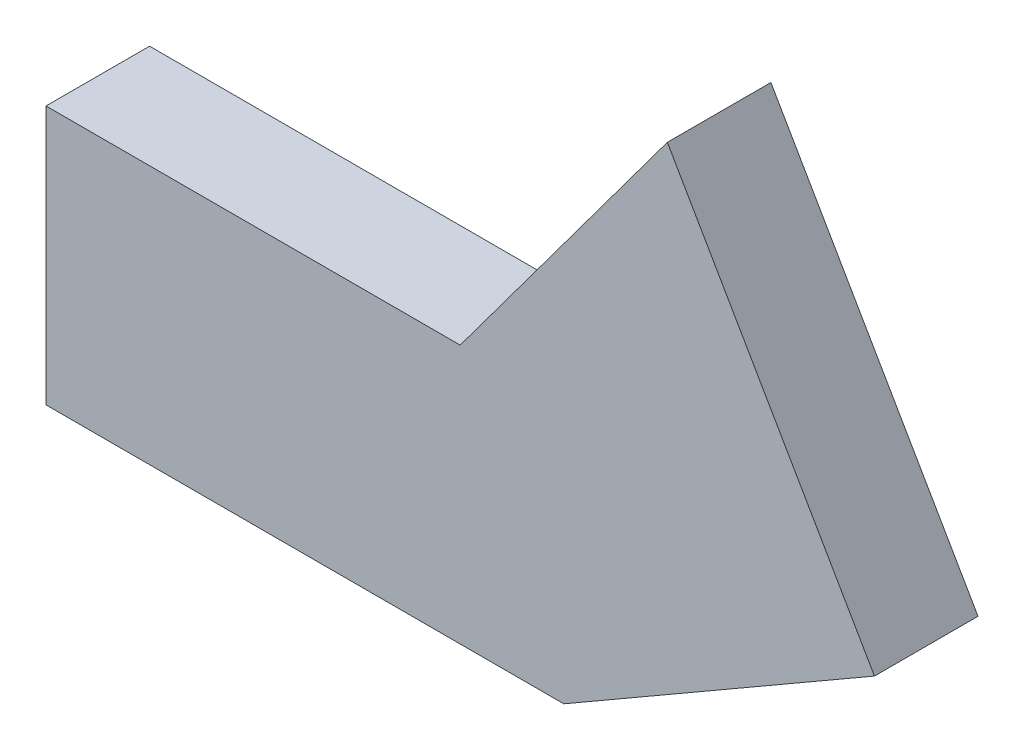
SolidWorks part; units mm, degrees
ref_plane "Front Plane" through (0, 0, 0) normal (0, 0, 1) x (1, 0, 0)
ref_plane "Top Plane" through (0, 0, 0) normal (0, 1, 0) x (1, 0, 0)
ref_plane "Right Plane" through (0, 0, 0) normal (1, 0, 0) x (0, 0, -1)
sketch "Sketch1" plane through (0, 0, 0) normal (0, 0, 1) x (1, 0, 0)
  line L7 (0, 0) -> (100, 0)
  line L8 (100, 0) -> (160, 34.641)
  line L9 (0, 0) -> (0, 50)
  line L10 (0, 50) -> (80, 50)
  line L11 (80, 50) -> (120, 103.923)
  line L12 (120, 103.923) -> (160, 34.641)
  point P2 (0, 0)
  point P3 (0, 0)
  dimension "D1" = 100
  dimension "D2" = 160
  dimension "D3" = 80
  dimension "D4" = 80
  dimension "D5" = 50
  dimension "D6" = 150
extrude "Boss-Extrude1" add sketch "Sketch1" along normal blind 20 contours L12 L8 L7 L9 L10 L11
